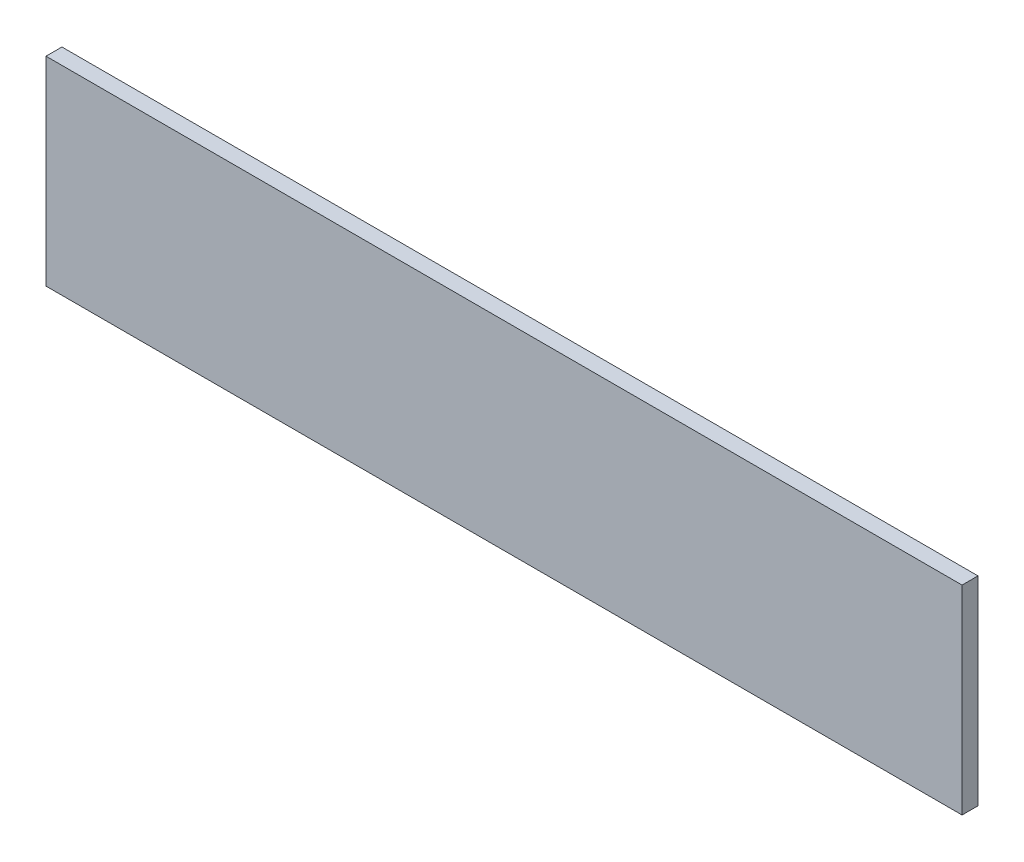
SolidWorks part; units mm, degrees
ref_plane "Front Plane" through (0, 0, 0) normal (0, 0, 1) x (1, 0, 0)
ref_plane "Top Plane" through (0, 0, 0) normal (0, 1, 0) x (1, 0, 0)
ref_plane "Right Plane" through (0, 0, 0) normal (1, 0, 0) x (0, 0, -1)
sketch "Sketch1" plane through (0, 0, 0) normal (0, 0, 1) x (1, 0, 0)
  line L0 (0, 0) -> (230, 0)
  line L1 (230, 0) -> (230, 50)
  line L2 (230, 50) -> (0, 50)
  line L3 (0, 50) -> (0, 0)
  dimension "D1" = 230
  dimension "D2" = 50
extrude "Boss-Extrude1" add sketch "Sketch1" along normal blind 4
